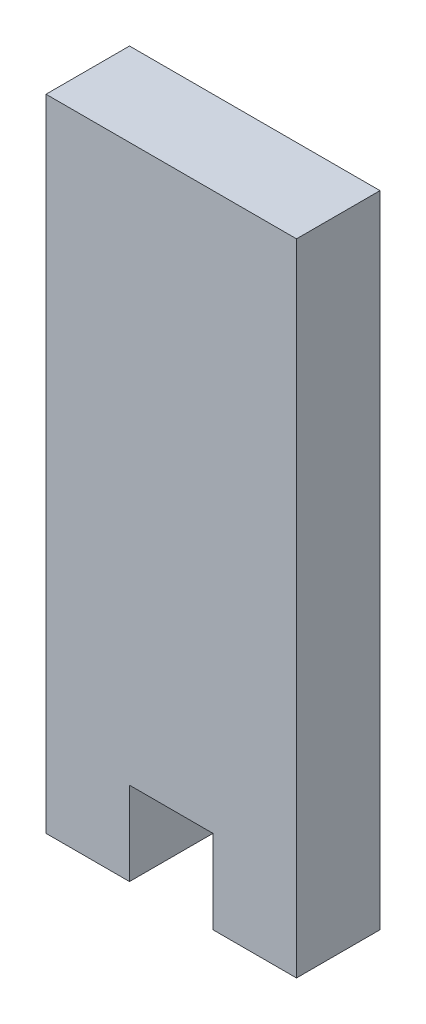
SolidWorks part; units mm, degrees
ref_plane "Front Plane" through (0, 0, 0) normal (0, 0, 1) x (1, 0, 0)
ref_plane "Top Plane" through (0, 0, 0) normal (0, 1, 0) x (1, 0, 0)
ref_plane "Right Plane" through (0, 0, 0) normal (1, 0, 0) x (0, 0, -1)
sketch "Sketch2" plane through (0, 0, 0) normal (0, 0, 1) x (1, 0, 0)
  line L0 (1.5953, -5.5375) -> (4.5953, -5.5375)
  line L1 (-4.4047, 17.4625) -> (4.5953, 17.4625)
  line L2 (-4.4047, 17.4625) -> (-4.4047, -5.5375)
  line L3 (-4.4047, -5.5375) -> (-1.4047, -5.5375)
  line L4 (4.5953, 17.4625) -> (4.5953, -5.5375)
  line L5 (-1.4047, -2.5375) -> (1.5953, -2.5375)
  line L6 (-1.4047, -2.5375) -> (-1.4047, -5.5375)
  line L7 (1.5953, -2.5375) -> (1.5953, -5.5375)
  dimension "D1" = 23
  dimension "D2" = 3
  dimension "D3" = 3
extrude "Boss-Extrude1" add sketch "Sketch2" along normal blind 3
